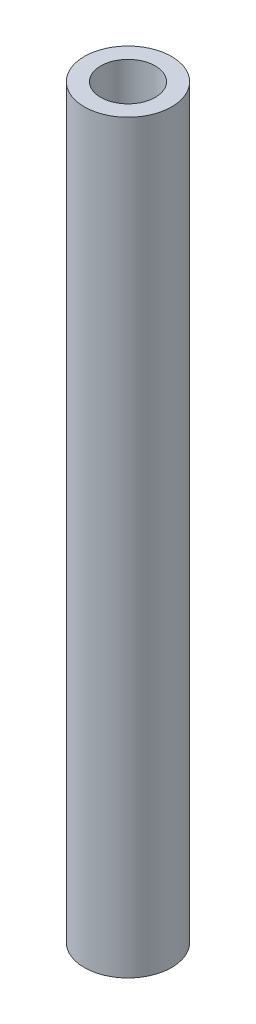
SolidWorks part; units mm, degrees
ref_plane "Front Plane" through (0, 0, 0) normal (0, 0, 1) x (1, 0, 0)
ref_plane "Top Plane" through (0, 0, 0) normal (0, 1, 0) x (1, 0, 0)
ref_plane "Right Plane" through (0, 0, 0) normal (1, 0, 0) x (0, 0, -1)
sketch "Szkic1" plane through (0, 0, 0) normal (0, 1, 0) x (1, 0, 0)
  circle A0 centre (-3.4437, 0) radius 2.5
  circle A1 centre (-3.4437, 0) radius 4
  dimension "D1" = 5
  dimension "D2" = 8
extrude "Dodanie-wyciągnięcie1" add sketch "Szkic1" along normal blind 68.3
